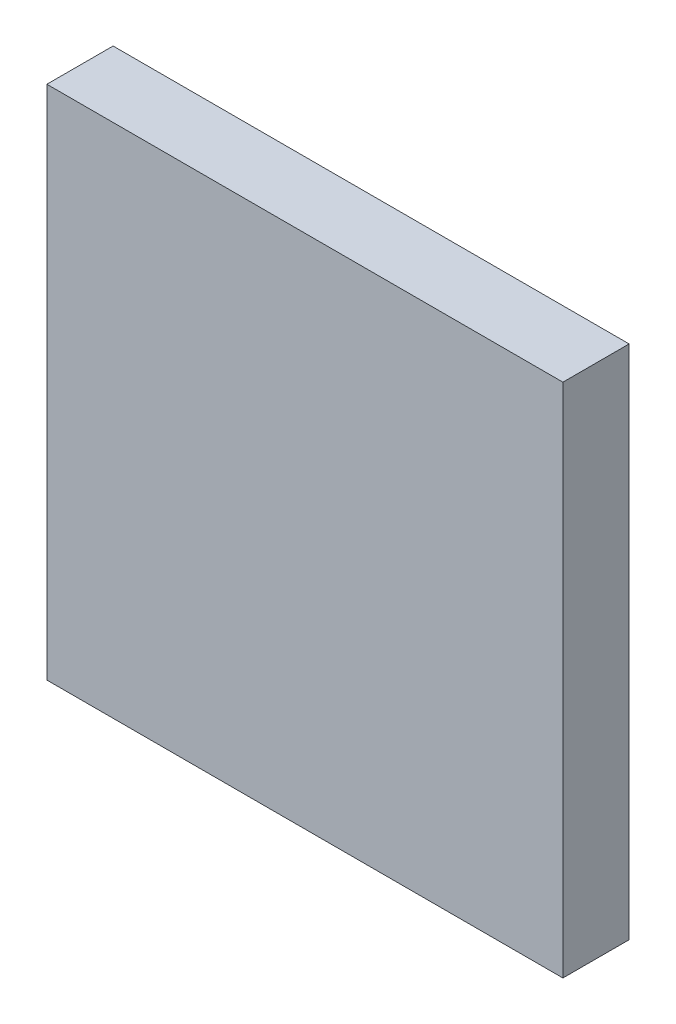
SolidWorks part; units mm, degrees
ref_plane "正面" through (0, 0, 0) normal (0, 0, 1) x (1, 0, 0)
ref_plane "平面" through (0, 0, 0) normal (0, 1, 0) x (1, 0, 0)
ref_plane "右側面" through (0, 0, 0) normal (1, 0, 0) x (0, 0, -1)
sketch "ｽｹｯﾁ1" plane through (0, 0, 0) normal (0, 0, 1) x (1, 0, 0)
  line L0 (-50, 0) -> (50, 0) construction
  line L1 (-50, 50) -> (50, 50)
  line L2 (-50, 50) -> (-50, -50)
  line L3 (-50, -50) -> (50, -50)
  line L4 (50, 50) -> (50, -50)
  line L5 (0, -50) -> (0, 50) construction
  point P8 (0, 0)
  dimension "D1" = 100
  dimension "D2" = 100
  dimension "D3" = 0
  dimension "D4" = 0
extrude "ﾎﾞｽ - 押し出し1" add sketch "ｽｹｯﾁ1" along normal blind 1.6
sketch "ｽｹｯﾁ4" plane through (0, 0, 0) normal (0, 0, -1) x (-1, 0, 0)
  line L0 (-50, -50) -> (-50, 50) construction
  line L1 (11.11, -41.35) -> (28.89, -41.35)
  line L2 (11.11, -41.35) -> (11.11, -43.85)
  line L3 (11.11, -43.85) -> (28.89, -43.85)
  line L4 (28.89, -41.35) -> (28.89, -43.85)
  line L5 (50, -50) -> (-50, -50) construction
  line L6 (50, 50) -> (50, -50) construction
  line L8 (-43.85, -11.11) -> (-41.35, -11.11)
  line L9 (-43.85, -11.11) -> (-43.85, -28.89)
  line L10 (-43.85, -28.89) -> (-41.35, -28.89)
  line L11 (-41.35, -11.11) -> (-41.35, -28.89)
  line L12 (-28.89, 43.85) -> (-11.11, 43.85)
  line L13 (-28.89, 43.85) -> (-28.89, 41.35)
  line L14 (-28.89, 41.35) -> (-11.11, 41.35)
  line L15 (-11.11, 43.85) -> (-11.11, 41.35)
  line L16 (-50, 50) -> (50, 50) construction
  line L18 (41.35, 28.89) -> (43.85, 28.89)
  line L19 (41.35, 28.89) -> (41.35, 11.11)
  line L20 (41.35, 11.11) -> (43.85, 11.11)
  line L21 (43.85, 28.89) -> (43.85, 11.11)
  point P4 (28.89, -42.6)
  point P7 (20, -43.85)
  point P14 (-43.85, -20)
  point P15 (-42.6, -28.89)
  point P22 (-28.89, 42.6)
  point P25 (43.85, 20)
  point P26 (-20, 43.85)
  point P31 (42.6, 28.89)
  dimension "D1" = 7.4
  dimension "D2" = 30
  dimension "D3" = 2.5
  dimension "D4" = 17.78
  dimension "D5" = 2.5
  dimension "D6" = 17.78
  dimension "D7" = 30
  dimension "D8" = 7.4
  dimension "D9" = 2.5
  dimension "D10" = 7.4
  dimension "D11" = 30
  dimension "D12" = 17.78
  dimension "D13" = 17.78
  dimension "D14" = 2.5
  dimension "D15" = 30
  dimension "D16" = 7.4
extrude "ﾎﾞｽ - 押し出し2" add sketch "ｽｹｯﾁ4" along normal blind 2.5
sketch "ｽｹｯﾁ5" plane through (0, 0, -2.5) normal (0, 0, -1) x (-1, 0, 0)
  line L1 (-20.32, 42.92) -> (-19.68, 42.92)
  line L2 (-20.32, 42.92) -> (-20.32, 42.28)
  line L3 (-20.32, 42.28) -> (-19.68, 42.28)
  line L4 (-19.68, 42.92) -> (-19.68, 42.28)
  line L5 (43.85, 28.89) -> (41.35, 28.89) construction
  line L6 (-11.11, 43.85) -> (-28.89, 43.85) construction
  line L7 (-28.89, 43.85) -> (-28.89, 41.35) construction
  line L8 (-43.85, -28.89) -> (-41.35, -28.89) construction
  line L9 (-17.78, 42.92) -> (-17.14, 42.92)
  line L10 (-17.78, 42.92) -> (-17.78, 42.28)
  line L11 (-17.78, 42.28) -> (-17.14, 42.28)
  line L12 (-17.14, 42.92) -> (-17.14, 42.28)
  line L13 (-15.24, 42.92) -> (-14.6, 42.92)
  line L14 (-15.24, 42.92) -> (-15.24, 42.28)
  line L15 (-15.24, 42.28) -> (-14.6, 42.28)
  line L16 (-14.6, 42.92) -> (-14.6, 42.28)
  line L17 (-12.7, 42.92) -> (-12.06, 42.92)
  line L18 (-12.7, 42.92) -> (-12.7, 42.28)
  line L19 (-12.7, 42.28) -> (-12.06, 42.28)
  line L20 (-12.06, 42.92) -> (-12.06, 42.28)
  line L21 (-22.86, 42.92) -> (-22.22, 42.92)
  line L22 (-22.86, 42.92) -> (-22.86, 42.28)
  line L23 (-22.86, 42.28) -> (-22.22, 42.28)
  line L24 (-22.22, 42.92) -> (-22.22, 42.28)
  line L25 (-25.4, 42.92) -> (-24.76, 42.92)
  line L26 (-25.4, 42.92) -> (-25.4, 42.28)
  line L27 (-25.4, 42.28) -> (-24.76, 42.28)
  line L28 (-24.76, 42.92) -> (-24.76, 42.28)
  line L29 (-27.94, 42.92) -> (-27.3, 42.92)
  line L30 (-27.94, 42.92) -> (-27.94, 42.28)
  line L31 (-27.94, 42.28) -> (-27.3, 42.28)
  line L32 (-27.3, 42.92) -> (-27.3, 42.28)
  line L33 (-42.92, -19.68) -> (-42.28, -19.68)
  line L34 (-42.92, -19.68) -> (-42.92, -20.32)
  line L35 (-42.92, -20.32) -> (-42.28, -20.32)
  line L36 (-42.28, -19.68) -> (-42.28, -20.32)
  line L37 (-43.85, -11.11) -> (-43.85, -28.89) construction
  line L38 (43.85, 11.11) -> (43.85, 28.89) construction
  line L39 (-42.92, -22.22) -> (-42.28, -22.22)
  line L40 (-42.92, -22.22) -> (-42.92, -22.86)
  line L41 (-42.92, -22.86) -> (-42.28, -22.86)
  line L42 (-42.28, -22.22) -> (-42.28, -22.86)
  line L44 (42.28, 19.68) -> (42.92, 19.68)
  line L45 (-42.92, -24.76) -> (-42.28, -24.76)
  line L46 (-42.92, -24.76) -> (-42.92, -25.4)
  line L47 (-42.92, -25.4) -> (-42.28, -25.4)
  line L48 (-42.28, -24.76) -> (-42.28, -25.4)
  line L49 (-42.92, -27.3) -> (-42.28, -27.3)
  line L50 (-42.92, -27.3) -> (-42.92, -27.94)
  line L51 (-42.92, -27.94) -> (-42.28, -27.94)
  line L52 (-42.28, -27.3) -> (-42.28, -27.94)
  line L53 (-42.92, -17.14) -> (-42.28, -17.14)
  line L54 (-42.92, -17.14) -> (-42.92, -17.78)
  line L55 (-42.92, -17.78) -> (-42.28, -17.78)
  line L56 (-42.28, -17.14) -> (-42.28, -17.78)
  line L57 (-42.92, -14.6) -> (-42.28, -14.6)
  line L58 (-42.92, -14.6) -> (-42.92, -15.24)
  line L59 (-42.92, -15.24) -> (-42.28, -15.24)
  line L60 (-42.28, -14.6) -> (-42.28, -15.24)
  line L61 (-42.92, -12.06) -> (-42.28, -12.06)
  line L62 (-42.92, -12.06) -> (-42.92, -12.7)
  line L63 (-42.92, -12.7) -> (-42.28, -12.7)
  line L64 (-42.28, -12.06) -> (-42.28, -12.7)
  line L69 (42.28, 19.68) -> (42.28, 20.32)
  line L70 (11.11, -43.85) -> (28.89, -43.85) construction
  line L71 (42.28, 17.78) -> (42.92, 17.78)
  line L72 (42.28, 20.32) -> (42.92, 20.32)
  line L73 (42.92, 19.68) -> (42.92, 20.32)
  line L75 (42.28, 17.78) -> (42.28, 17.14)
  line L76 (42.28, 17.14) -> (42.92, 17.14)
  line L77 (42.92, 17.78) -> (42.92, 17.14)
  line L78 (42.28, 15.24) -> (42.92, 15.24)
  line L79 (42.28, 15.24) -> (42.28, 14.6)
  line L80 (42.28, 14.6) -> (42.92, 14.6)
  line L81 (42.92, 15.24) -> (42.92, 14.6)
  line L82 (42.28, 12.7) -> (42.92, 12.7)
  line L83 (42.28, 12.7) -> (42.28, 12.06)
  line L84 (42.28, 12.06) -> (42.92, 12.06)
  line L85 (42.92, 12.7) -> (42.92, 12.06)
  line L86 (42.28, 22.86) -> (42.92, 22.86)
  line L87 (42.28, 22.86) -> (42.28, 22.22)
  line L88 (42.28, 22.22) -> (42.92, 22.22)
  line L89 (42.92, 22.86) -> (42.92, 22.22)
  line L90 (42.28, 25.4) -> (42.92, 25.4)
  line L91 (42.28, 25.4) -> (42.28, 24.76)
  line L92 (42.28, 24.76) -> (42.92, 24.76)
  line L93 (42.92, 25.4) -> (42.92, 24.76)
  line L94 (42.28, 27.94) -> (42.92, 27.94)
  line L95 (42.28, 27.94) -> (42.28, 27.3)
  line L96 (42.28, 27.3) -> (42.92, 27.3)
  line L97 (42.92, 27.94) -> (42.92, 27.3)
  line L98 (19.68, -42.28) -> (20.32, -42.28)
  line L99 (19.68, -42.28) -> (19.68, -42.92)
  line L100 (19.68, -42.92) -> (20.32, -42.92)
  line L101 (20.32, -42.28) -> (20.32, -42.92)
  line L102 (11.11, -41.35) -> (11.11, -43.85) construction
  line L104 (17.14, -42.28) -> (17.78, -42.28)
  line L105 (17.14, -42.28) -> (17.14, -42.92)
  line L106 (17.14, -42.92) -> (17.78, -42.92)
  line L107 (17.78, -42.28) -> (17.78, -42.92)
  line L108 (14.6, -42.28) -> (15.24, -42.28)
  line L109 (14.6, -42.28) -> (14.6, -42.92)
  line L110 (14.6, -42.92) -> (15.24, -42.92)
  line L111 (15.24, -42.28) -> (15.24, -42.92)
  line L112 (12.06, -42.28) -> (12.7, -42.28)
  line L113 (12.06, -42.28) -> (12.06, -42.92)
  line L114 (12.06, -42.92) -> (12.7, -42.92)
  line L115 (12.7, -42.28) -> (12.7, -42.92)
  line L116 (22.22, -42.28) -> (22.86, -42.28)
  line L117 (22.22, -42.28) -> (22.22, -42.92)
  line L118 (22.22, -42.92) -> (22.86, -42.92)
  line L119 (22.86, -42.28) -> (22.86, -42.92)
  line L120 (24.76, -42.28) -> (25.4, -42.28)
  line L121 (24.76, -42.28) -> (24.76, -42.92)
  line L122 (24.76, -42.92) -> (25.4, -42.92)
  line L123 (25.4, -42.28) -> (25.4, -42.92)
  line L124 (27.3, -42.28) -> (27.94, -42.28)
  line L125 (27.3, -42.28) -> (27.3, -42.92)
  line L126 (27.3, -42.92) -> (27.94, -42.92)
  line L127 (27.94, -42.28) -> (27.94, -42.92)
  point P4 (-20, 42.92)
  point P7 (-20, 43.85)
  point P8 (-20.32, 42.6)
  point P11 (-28.89, 42.6)
  point P16 (-20, 42.28)
  point P17 (-17.46, 42.28)
  point P22 (-14.92, 42.28)
  point P27 (-12.38, 42.28)
  point P40 (-22.54, 42.28)
  point P41 (-25.08, 42.28)
  point P42 (-27.62, 42.28)
  point P47 (-42.6, -20.32)
  point P50 (-42.6, -28.89)
  point P53 (-42.92, -20)
  point P54 (-43.85, -20)
  point P59 (-42.28, -22.54)
  point P60 (-42.28, -20)
  point P61 (-42.28, -25.08)
  point P70 (-42.28, -27.62)
  point P83 (-42.28, -17.46)
  point P84 (-42.28, -14.92)
  point P85 (-42.28, -12.38)
  point P90 (42.6, 19.68)
  point P93 (42.6, 28.89)
  point P94 (42.92, 20)
  point P97 (43.85, 20)
  point P110 (42.28, 12.38)
  point P111 (42.28, 14.92)
  point P112 (42.28, 17.46)
  point P113 (42.28, 20)
  point P126 (42.28, 22.54)
  point P127 (42.28, 25.08)
  point P128 (42.28, 27.62)
  point P133 (20, -42.92)
  point P136 (20, -43.85)
  point P139 (11.11, -42.6)
  point P140 (19.68, -42.6)
  point P165 (17.46, -42.28)
  point P166 (20, -42.28)
  point P167 (14.92, -42.28)
  point P168 (12.38, -42.28)
  point P169 (22.54, -42.28)
  point P170 (25.08, -42.28)
  point P171 (27.62, -42.28)
  point P173 (12.06, -42.6)
  point P174 (14.6, -42.6)
  point P175 (17.14, -42.6)
  point P176 (22.22, -42.6)
  point P177 (24.76, -42.6)
  point P178 (27.3, -42.6)
  point P179 (-42.6, -27.3)
  point P180 (-42.6, -24.76)
  point P181 (-42.6, -22.22)
  point P182 (-42.6, -19.68)
  point P183 (-42.6, -17.14)
  point P184 (-42.6, -14.6)
  point P185 (-42.6, -12.06)
  point P186 (-27.94, 42.6)
  point P187 (-25.4, 42.6)
  point P188 (-22.86, 42.6)
  point P189 (-17.78, 42.6)
  point P190 (-15.24, 42.6)
  point P191 (-12.7, 42.6)
  point P192 (42.6, 15.24)
  point P193 (42.6, 17.78)
  point P194 (42.6, 20.32)
  point P195 (42.6, 22.86)
  point P196 (42.6, 25.4)
  point P197 (42.6, 27.94)
  point P198 (42.6, 12.7)
  dimension "D1" = 0.64
  dimension "D2" = 0.64
  dimension "D3" = 0.64
  dimension "D4" = 0.64
  dimension "D5" = 2.54
  dimension "D6" = 0.64
  dimension "D7" = 2.54
  dimension "D8" = 0.64
  dimension "D9" = 0.64
  dimension "D10" = 0.64
  dimension "D11" = 2.54
  dimension "D12" = 0.64
  dimension "D13" = 0.64
  dimension "D14" = 0.64
  dimension "D15" = 2.54
  dimension "D16" = 0.64
  dimension "D17" = 0.64
  dimension "D18" = 0.64
  dimension "D19" = 2.54
  dimension "D20" = 2.54
  dimension "D21" = 0.64
  dimension "D22" = 0.64
  dimension "D23" = 0.64
  dimension "D24" = 0.64
  dimension "D25" = 2.54
  dimension "D26" = 0.64
  dimension "D27" = 2.54
  dimension "D28" = 0.64
  dimension "D29" = 2.54
  dimension "D30" = 0.64
  dimension "D31" = 0.64
  dimension "D32" = 0.64
  dimension "D33" = 0.64
  dimension "D34" = 2.54
  dimension "D35" = 2.54
  dimension "D36" = 0.64
  dimension "D37" = 0.64
  dimension "D38" = 0.64
  dimension "D39" = 2.54
  dimension "D40" = 0.64
  dimension "D41" = 0.64
  dimension "D42" = 0.64
  dimension "D43" = 0.64
  dimension "D44" = 0.64
  dimension "D45" = 0.64
  dimension "D46" = 2.54
  dimension "D47" = 2.54
  dimension "D48" = 2.54
  dimension "D49" = 2.54
  dimension "D50" = 0.64
  dimension "D51" = 0.64
  dimension "D52" = 0.64
  dimension "D53" = 0.64
  dimension "D54" = 2.54
  dimension "D55" = 0.64
  dimension "D56" = 0.64
  dimension "D57" = 2.54
  dimension "D58" = 0.64
  dimension "D59" = 0.64
  dimension "D60" = 0.64
  dimension "D61" = 0.64
  dimension "D62" = 0.64
  dimension "D63" = 2.54
  dimension "D64" = 2.54
  dimension "D65" = 2.54
  dimension "D66" = 0.64
  dimension "D67" = 0.64
  dimension "D68" = 0.64
  dimension "D69" = 0.64
  dimension "D70" = 0.64
  dimension "D71" = 0.64
  dimension "D72" = 2.54
  dimension "D73" = 2.54
  dimension "D74" = 2.54
  dimension "D75" = 0.64
  dimension "D76" = 0.64
  dimension "D77" = 0.64
  dimension "D78" = 0.64
  dimension "D79" = 0.64
  dimension "D80" = 0.64
extrude "ﾎﾞｽ - 押し出し3" add sketch "ｽｹｯﾁ5" along normal blind 6.1
sketch "ｽｹｯﾁ6" plane through (0, 0, 1.6) normal (0, 0, 1) x (1, 0, 0)
  line L0 (-50, -50) -> (50, -50) construction
  line L1 (-36.74, -33.26) -> (-33.26, -33.26)
  line L2 (-36.74, -33.26) -> (-36.74, -36.74)
  line L3 (-36.74, -36.74) -> (-33.26, -36.74)
  line L4 (-33.26, -33.26) -> (-33.26, -36.74)
  line L5 (-50, 50) -> (-50, -50) construction
  line L6 (50, 50) -> (-50, 50) construction
  line L7 (-36.74, 36.74) -> (-33.26, 36.74)
  line L8 (-36.74, 36.74) -> (-36.74, 33.26)
  line L9 (-36.74, 33.26) -> (-33.26, 33.26)
  line L10 (-33.26, 36.74) -> (-33.26, 33.26)
  line L11 (50, -50) -> (50, 50) construction
  line L12 (33.26, -33.26) -> (36.74, -33.26)
  line L13 (33.26, -33.26) -> (33.26, -36.74)
  line L14 (33.26, -36.74) -> (36.74, -36.74)
  line L15 (36.74, -33.26) -> (36.74, -36.74)
  line L17 (33.26, 36.74) -> (36.74, 36.74)
  line L18 (33.26, 36.74) -> (33.26, 33.26)
  line L19 (33.26, 33.26) -> (36.74, 33.26)
  line L20 (36.74, 36.74) -> (36.74, 33.26)
  point P4 (-36.74, -35)
  point P7 (-35, -36.74)
  point P14 (-36.74, 35)
  point P17 (-35, 36.74)
  point P22 (35, -36.74)
  point P25 (36.74, -35)
  point P30 (35, 36.74)
  point P31 (36.74, 35)
  dimension "D1" = 3.48
  dimension "D2" = 3.48
  dimension "D3" = 15
  dimension "D4" = 15
  dimension "D5" = 3.48
  dimension "D6" = 3.48
  dimension "D7" = 15
  dimension "D8" = 15
  dimension "D9" = 15
  dimension "D10" = 15
  dimension "D11" = 3.48
  dimension "D12" = 3.48
  dimension "D13" = 15
  dimension "D14" = 15
  dimension "D15" = 3.48
  dimension "D16" = 3.48
extrude "ﾎﾞｽ - 押し出し4" add sketch "ｽｹｯﾁ6" along normal blind 2
sketch "ｽｹｯﾁ7" plane through (0, 0, 1.6) normal (0, 0, 1) x (1, 0, 0)
  line L0 (-50, -50) -> (50, -50) construction
  line L1 (-38.5, 2) -> (-36.5, 2)
  line L2 (-38.5, 2) -> (-38.5, -2)
  line L3 (-38.5, -2) -> (-36.5, -2)
  line L4 (-36.5, 2) -> (-36.5, -2)
  line L5 (-50, 50) -> (-50, -50) construction
  line L6 (50, -50) -> (50, 50) construction
  line L7 (36.5, 2) -> (38.5, 2)
  line L8 (36.5, 2) -> (36.5, -2)
  line L9 (36.5, -2) -> (38.5, -2)
  line L10 (38.5, 2) -> (38.5, -2)
  line L11 (50, 50) -> (-50, 50) construction
  line L12 (-2, 38.5) -> (2, 38.5)
  line L13 (-2, 38.5) -> (-2, 36.5)
  line L14 (-2, 36.5) -> (2, 36.5)
  line L15 (2, 38.5) -> (2, 36.5)
  line L17 (-2, -36.5) -> (2, -36.5)
  line L18 (-2, -36.5) -> (-2, -38.5)
  line L19 (-2, -38.5) -> (2, -38.5)
  line L20 (2, -36.5) -> (2, -38.5)
  line L21 (-1, 2) -> (1, 2)
  line L22 (-1, 2) -> (-1, -2)
  line L23 (-1, -2) -> (1, -2)
  line L24 (1, 2) -> (1, -2)
  point P4 (-38.5, 0)
  point P7 (-37.5, -2)
  point P14 (37.5, 2)
  point P17 (38.5, 0)
  point P22 (-2, 37.5)
  point P25 (0, 38.5)
  point P30 (-2, -37.5)
  point P31 (0, -38.5)
  point P36 (1, 0)
  point P37 (36.5, 0)
  point P38 (0, 36.5)
  point P39 (0, 2)
  dimension "D1" = 4
  dimension "D2" = 2
  dimension "D3" = 50
  dimension "D4" = 12.5
  dimension "D5" = 4
  dimension "D6" = 2
  dimension "D7" = 12.5
  dimension "D8" = 50
  dimension "D9" = 4
  dimension "D10" = 2
  dimension "D11" = 12.5
  dimension "D12" = 50
  dimension "D13" = 4
  dimension "D14" = 2
  dimension "D15" = 12.5
  dimension "D16" = 50
  dimension "D17" = 4
  dimension "D18" = 2
extrude "ﾎﾞｽ - 押し出し5" add sketch "ｽｹｯﾁ7" along normal blind 1.1
sketch "ｽｹｯﾁ8" plane through (0, 0, 1.6) normal (0, 0, 1) x (1, 0, 0)
  line L0 (-50, -50) -> (50, -50) construction
  line L1 (-7.6, -13.3) -> (7.6, -13.3)
  line L2 (-7.6, -13.3) -> (-7.6, -20.7)
  line L3 (-7.6, -20.7) -> (7.6, -20.7)
  line L4 (7.6, -13.3) -> (7.6, -20.7)
  point P4 (-7.6, -17)
  point P7 (0, -50)
  point P8 (0, -20.7)
  dimension "D1" = 7.4
  dimension "D2" = 15.2
  dimension "D3" = 33
extrude "ﾎﾞｽ - 押し出し6" add sketch "ｽｹｯﾁ8" along normal blind 2.65
sketch "ｽｹｯﾁ9" plane through (0, 0, 0) normal (0, 0, -1) x (-1, 0, 0)
  line L1 (-4.61, 19.83) -> (3.01, 19.83)
  line L2 (-4.61, 19.83) -> (-4.61, 17.33)
  line L3 (-4.61, 17.33) -> (3.01, 17.33)
  line L4 (3.01, 19.83) -> (3.01, 17.33)
  line L5 (50, 50) -> (50, -50) construction
  line L6 (50, -50) -> (-50, -50) construction
  point P4 (-0.8, 19.83)
  point P7 (3.01, 18.58)
  dimension "D1" = 7.62
  dimension "D2" = 2.5
  dimension "D3" = 50.8
  dimension "D4" = 68.58
extrude "ﾎﾞｽ - 押し出し7" add sketch "ｽｹｯﾁ9" along normal blind 2.5
sketch "ｽｹｯﾁ11" plane through (0, 0, -2.5) normal (0, 0, -1) x (-1, 0, 0)
  line L0 (3.01, 19.83) -> (-4.61, 19.83) construction
  line L1 (-1.12, 18.9) -> (-0.48, 18.9)
  line L2 (-1.12, 18.9) -> (-1.12, 18.26)
  line L3 (-1.12, 18.26) -> (-0.48, 18.26)
  line L4 (-0.48, 18.9) -> (-0.48, 18.26)
  line L5 (-4.61, 19.83) -> (-4.61, 17.33) construction
  line L7 (-3.66, 18.9) -> (-3.02, 18.9)
  line L8 (-3.66, 18.9) -> (-3.66, 18.26)
  line L9 (-3.66, 18.26) -> (-3.02, 18.26)
  line L10 (-3.02, 18.9) -> (-3.02, 18.26)
  line L11 (1.42, 18.9) -> (2.06, 18.9)
  line L12 (1.42, 18.9) -> (1.42, 18.26)
  line L13 (1.42, 18.26) -> (2.06, 18.26)
  line L14 (2.06, 18.9) -> (2.06, 18.26)
  point P4 (-0.8, 18.9)
  point P7 (-0.8, 19.83)
  point P8 (-1.12, 18.58)
  point P11 (-4.61, 18.58)
  point P20 (-3.34, 18.26)
  point P21 (-0.8, 18.26)
  point P22 (1.74, 18.26)
  point P23 (-3.66, 18.58)
  point P25 (1.42, 18.58)
  dimension "D1" = 0.64
  dimension "D2" = 0.64
  dimension "D3" = 0.64
  dimension "D4" = 0.64
  dimension "D5" = 0.64
  dimension "D6" = 2.54
  dimension "D7" = 2.54
extrude "ﾎﾞｽ - 押し出し8" add sketch "ｽｹｯﾁ11" along normal blind 6.1
sketch "ｽｹｯﾁ16" plane through (0, 0, 0) normal (0, 0, -1) x (-1, 0, 0)
  line L0 (50, -50) -> (-50, -50) construction
  line L1 (-5.08, -29.75) -> (5.08, -29.75)
  line L2 (-5.08, -29.75) -> (-5.08, -32.25)
  line L3 (-5.08, -32.25) -> (5.08, -32.25)
  line L4 (5.08, -29.75) -> (5.08, -32.25)
  line L5 (0, 0) -> (0, -50) construction
  point P4 (-5.08, -31)
  point P10 (0, -32.25)
  dimension "D1" = 2.5
  dimension "D2" = 10.16
  dimension "D3" = 19
extrude "ﾎﾞｽ - 押し出し12" add sketch "ｽｹｯﾁ16" along normal blind 2.5
sketch "ｽｹｯﾁ17" plane through (0, 0, -2.5) normal (0, 0, -1) x (-1, 0, 0)
  line L0 (-5.08, -31) -> (5.08, -31) construction
  line L1 (-4.13, -30.68) -> (-3.49, -30.68)
  line L2 (-4.13, -30.68) -> (-4.13, -31.32)
  line L3 (-4.13, -31.32) -> (-3.49, -31.32)
  line L4 (-3.49, -30.68) -> (-3.49, -31.32)
  line L5 (-1.59, -30.68) -> (-0.95, -30.68)
  line L6 (-1.59, -30.68) -> (-1.59, -31.32)
  line L7 (-1.59, -31.32) -> (-0.95, -31.32)
  line L8 (-0.95, -30.68) -> (-0.95, -31.32)
  line L9 (0.95, -30.68) -> (1.59, -30.68)
  line L10 (0.95, -30.68) -> (0.95, -31.32)
  line L11 (0.95, -31.32) -> (1.59, -31.32)
  line L12 (1.59, -30.68) -> (1.59, -31.32)
  line L13 (3.49, -30.68) -> (4.13, -30.68)
  line L14 (3.49, -30.68) -> (3.49, -31.32)
  line L15 (3.49, -31.32) -> (4.13, -31.32)
  line L16 (4.13, -30.68) -> (4.13, -31.32)
  line L17 (-5.08, -29.75) -> (-5.08, -32.25) construction
  line L18 (5.08, -32.25) -> (5.08, -29.75) construction
  point P22 (-4.13, -31)
  point P23 (-1.59, -31)
  point P24 (0.95, -31)
  point P25 (3.49, -31)
  point P26 (-3.81, -31.32)
  point P27 (-1.27, -31.32)
  point P28 (3.81, -31.32)
  point P29 (1.27, -31.32)
  dimension "D1" = 0.64
  dimension "D2" = 0.64
  dimension "D3" = 0.64
  dimension "D4" = 0.64
  dimension "D5" = 0.64
  dimension "D6" = 2.54
  dimension "D7" = 2.54
  dimension "D8" = 2.54
  dimension "D9" = 1.27
extrude "ﾎﾞｽ - 押し出し13" add sketch "ｽｹｯﾁ17" along normal blind 6.1
sketch "ｽｹｯﾁ15" plane through (0, 0, -2.5) normal (0, 0, -1) x (-1, 0, 0)
  line L1 (-60, 60) -> (60, 60)
  line L2 (-60, 60) -> (-60, -60)
  line L3 (-60, -60) -> (60, -60)
  line L4 (60, 60) -> (60, -60)
  point P4 (0, 60)
  point P6 (-60, 0)
  dimension "D1" = 120
  dimension "D2" = 120
extrude "ﾎﾞｽ - 押し出し11" add sketch "ｽｹｯﾁ15" against normal blind 15.4 separate body
